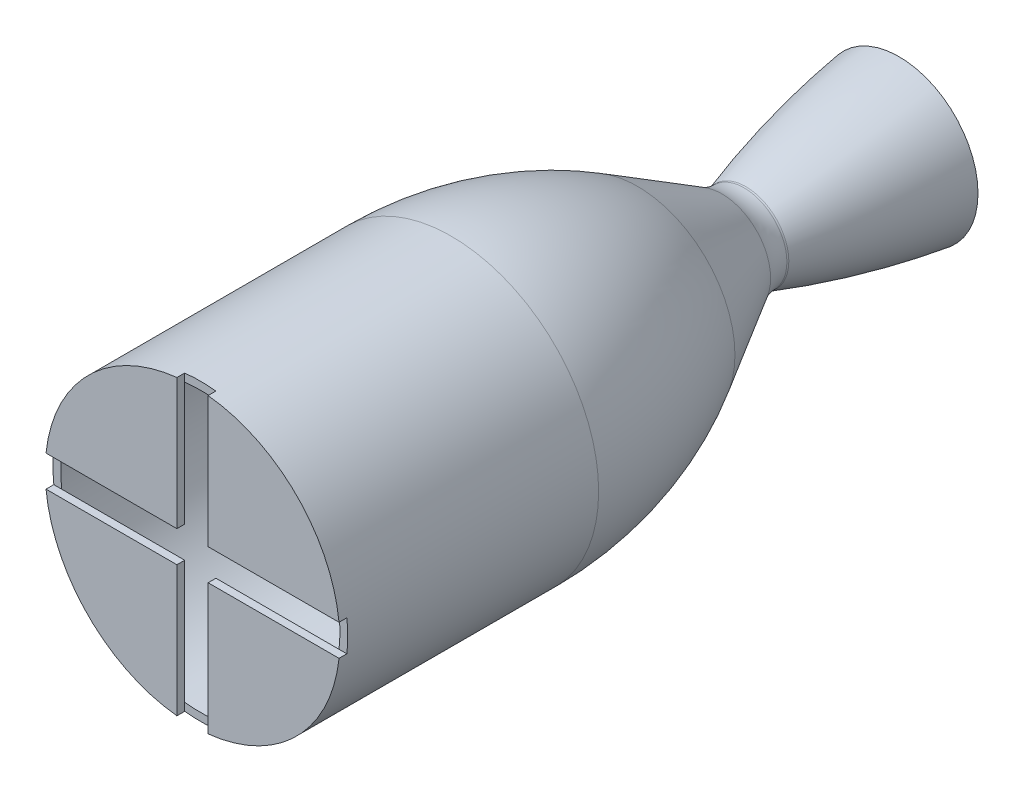
SolidWorks part; units mm, degrees
material "AISI 316 Stainless Steel Sheet (SS)"
ref_plane "Front Plane" through (0, 0, 0) normal (0, 0, 1) x (1, 0, 0)
ref_plane "Top Plane" through (0, 0, 0) normal (0, 1, 0) x (1, 0, 0)
ref_plane "Right Plane" through (0, 0, 0) normal (1, 0, 0) x (0, 0, -1)
sketch "Sketch2" plane through (0, 0, 0) normal (1, 0, 0) x (0, 0, -1)
  line L0 (0, 0) -> (0, 56.769)
  line L1 (0, 56.769) -> (102.108, 56.769)
  line L2 (222.9104, 14.492) -> (242.3075, 20.8844) construction
  line L3 (0, 0) -> (284.734, 0) construction
  line L4 (284.734, 28.956) -> (284.734, 0) construction
  line L6 (176.276, 36.8957) -> (210.5936, 17.0825)
  arc A0 (102.108, 56.769) -> (176.276, 36.8957) centre (102.108, -91.567) cw
  arc A1 (210.5936, 17.0825) -> (221.234, 14.224) centre (221.2616, 35.56) ccw
  arc A2 (221.234, 14.224) -> (222.9104, 14.492) centre (221.2409, 19.558) ccw
  arc A3 (222.9104, 14.492) -> (284.734, 28.956) centre (335.3024, -326.5475) cw
  dimension "D1" = 56.769
  dimension "D3" = 30
  dimension "D4" = 21.336
  dimension "D5" = 28.956
  dimension "D9" = 148.336
  dimension "D6" = 5.334
  dimension "D2" = 102.108
  dimension "D7" = 221.234
  dimension "D8" = 63.5
  dimension "D10" = 14.224
  dimension "D11" = 18.24
revolve "Revolve-Thin4" add sketch "Sketch2" angle 360 about L3 wall 3.175
sketch "Sketch4" plane through (0, 0, 0) normal (1, 0, 0) x (0, 0, -1)
  line L0 (-3.175, 59.944) -> (-3.175, -59.944) construction
  line L1 (-3.175, 6.35) -> (0, 6.35)
  line L2 (-3.175, 6.35) -> (-3.175, -6.35)
  line L3 (-3.175, -6.35) -> (0, -6.35)
  line L4 (0, 6.35) -> (0, -6.35)
  dimension "D1" = 12.7
extrude "Cut-Extrude1" cut sketch "Sketch4" against normal through all both and the other way through all
pattern_circular "CirPattern1" count 2 every 90 about axis through (0, 0, 3.175) along (0, 0, 1) of "Cut-Extrude1"
